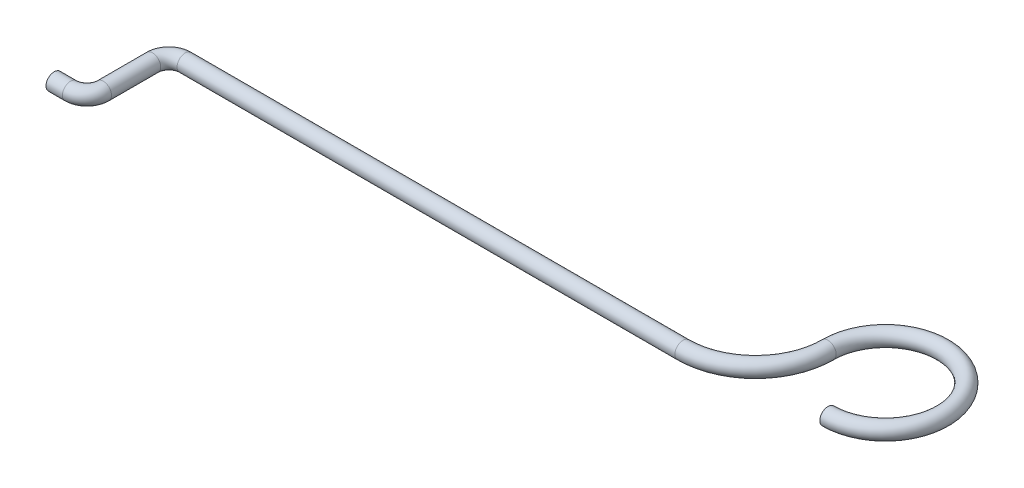
SolidWorks part; units mm, degrees
material "Stainless Steel (ferritic)"
ref_plane "Front" through (0, 0, 0) normal (0, 0, 1) x (1, 0, 0)
ref_plane "Top" through (0, 0, 0) normal (0, 1, 0) x (1, 0, 0)
ref_plane "Right" through (0, 0, 0) normal (1, 0, 0) x (0, 0, -1)
sketch "Sketch1" plane through (0, 0, 0) normal (0, 1, 0) x (1, 0, 0)
  line L0 (2, 1) -> (2, 4)
  line L1 (3, 5) -> (33.3835, 5)
  line L4 (1, 0) -> (0, 0)
  arc A0 (2, 4) -> (3, 5) centre (3, 4) cw
  arc A1 (33.3835, 5) -> (37.8055, 9.422) centre (33.3835, 9.422) ccw
  arc A3 (2, 1) -> (1, 0) centre (1, 1) cw
  arc A4 (37.8055, 9.422) -> (41.3055, 5.922) centre (41.3055, 9.422) cw
  dimension "D2" = 1
  dimension "D1" = 3.5
  dimension "D3" = 3
  dimension "D4" = 1
sketch "Sketch2" plane through (0, 0, 0) normal (1, 0, 0) x (0, 0, -1)
  circle A0 centre (0, 0) radius 0.5
  dimension "D1" = 1
sweep "Sweep1" add profiles "Sketch2" path "Sketch1"
